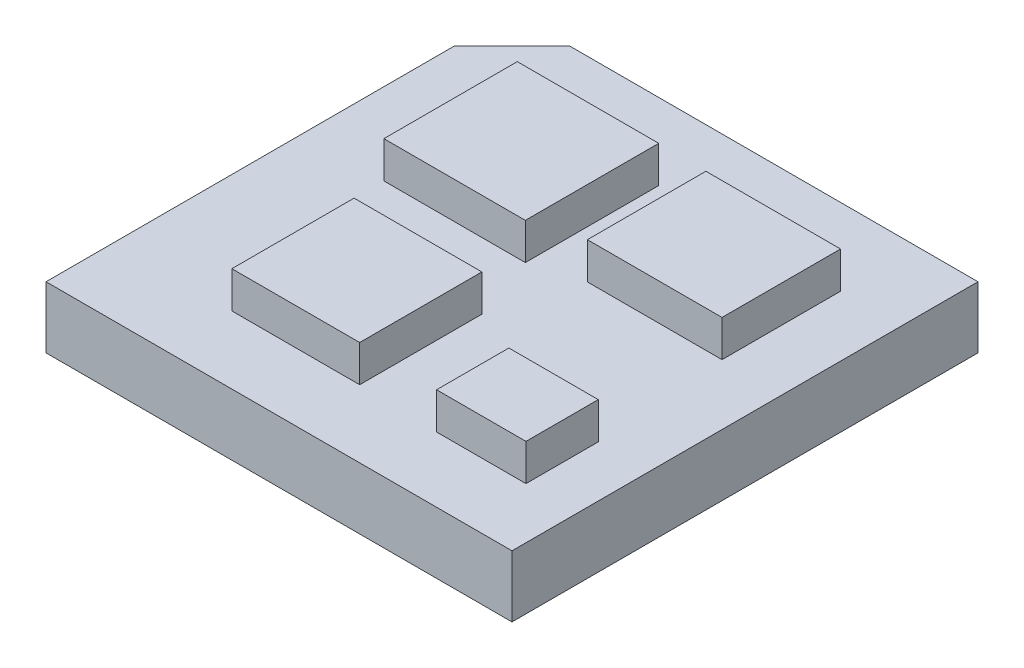
SolidWorks part; units mm, degrees
ref_plane "정면" through (0, 0, 0) normal (0, 0, 1) x (1, 0, 0)
ref_plane "윗면" through (0, 0, 0) normal (0, 1, 0) x (1, 0, 0)
ref_plane "우측면" through (0, 0, 0) normal (1, 0, 0) x (0, 0, -1)
sketch "스케치1" plane through (0, 0, 0) normal (0, 1, 0) x (1, 0, 0)
  line L0 (0, 10.6) -> (1.5, 12.1)
  line L1 (0, 0) -> (12.1, 0)
  line L2 (0, 0) -> (0, 10.6)
  line L3 (1.5, 12.1) -> (12.1, 12.1)
  line L4 (12.1, 0) -> (12.1, 12.1)
  point P2 (0, 12.1)
  dimension "D1" = 12.1
  dimension "D2" = 12.1
extrude "보스-돌출1" add sketch "스케치1" along normal blind 1.6
sketch "스케치2" plane through (0, 1.6, 0) normal (0, 1, 0) x (1, 0, 0)
  line L1 (2.1189, 10.118) -> (5.7922, 10.118)
  line L2 (2.1189, 10.118) -> (2.1189, 6.6542)
  line L3 (2.1189, 6.6542) -> (5.7922, 6.6542)
  line L4 (5.7922, 10.118) -> (5.7922, 6.6542)
  line L5 (7.0328, 10.1019) -> (10.5289, 10.1019)
  line L6 (7.0328, 10.1019) -> (7.0328, 7.0247)
  line L7 (7.0328, 7.0247) -> (10.5289, 7.0247)
  line L8 (10.5289, 10.1019) -> (10.5289, 7.0247)
  line L9 (3.0695, 4.9303) -> (6.3883, 4.9303)
  line L10 (3.0695, 4.9303) -> (3.0695, 1.7564)
  line L11 (3.0695, 1.7564) -> (6.3883, 1.7564)
  line L12 (6.3883, 4.9303) -> (6.3883, 1.7564)
  line L13 (8.4494, 3.5696) -> (10.7705, 3.5696)
  line L14 (8.4494, 3.5696) -> (8.4494, 1.692)
  line L15 (8.4494, 1.692) -> (10.7705, 1.692)
  line L16 (10.7705, 3.5696) -> (10.7705, 1.692)
extrude "보스-돌출2" add sketch "스케치2" along normal blind 0.95
